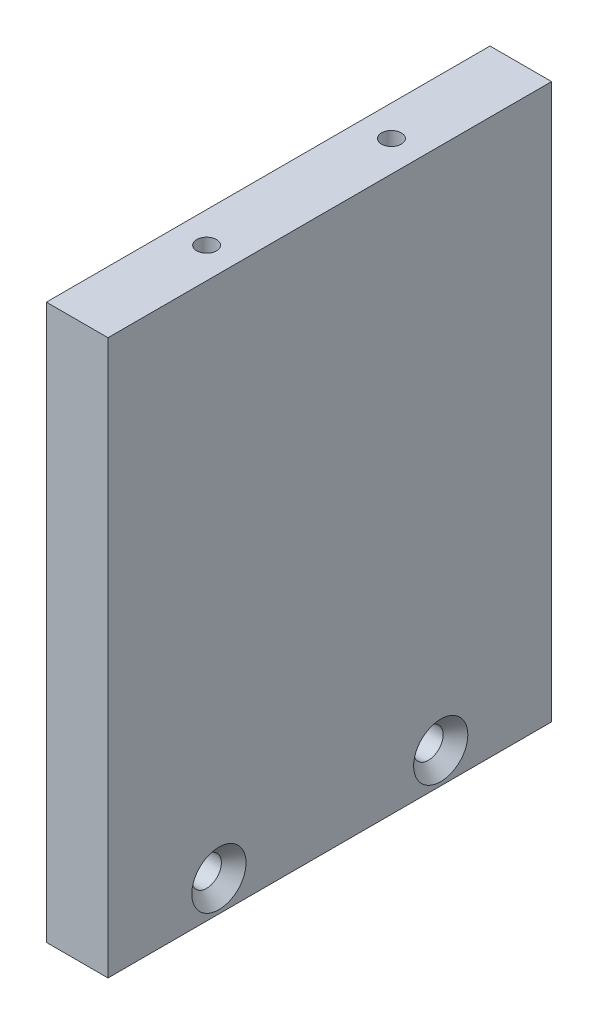
SolidWorks part; units mm, degrees
ref_plane "Front Plane" through (0, 0, 0) normal (0, 0, 1) x (1, 0, 0)
ref_plane "Top Plane" through (0, 0, 0) normal (0, 1, 0) x (1, 0, 0)
ref_plane "Right Plane" through (0, 0, 0) normal (1, 0, 0) x (0, 0, -1)
sketch "Sketch1" plane through (0, 0, 0) normal (1, 0, 0) x (0, 0, -1)
  line L1 (18, -22.5) -> (-18, -22.5)
  line L2 (18, -22.5) -> (18, 22.5)
  line L3 (18, 22.5) -> (-18, 22.5)
  line L4 (-18, -22.5) -> (-18, 22.5)
  line L5 (18, -22.5) -> (-18, 22.5) construction
  line L6 (18, 22.5) -> (-18, -22.5) construction
  point P0 (0, 0)
  dimension "D1" = 45
  dimension "D2" = 36
extrude "Boss-Extrude1" add sketch "Sketch1" along normal blind 5
sketch "Sketch2" plane through (0, 22.5, 0) normal (0, 1, 0) x (1, 0, 0)
  line L0 (2.5, 18) -> (2.5, -18) construction
  line L1 (5, 18) -> (0, 18) construction
  line L2 (5, -18) -> (0, -18) construction
  line L3 (0, 0) -> (5, 0) construction
  line L4 (5, 18) -> (5, -18) construction
  point P11 (2.5, 7.5)
  point P12 (2.5, -7.5)
  dimension "D1" = 7.5
hole_wizard "M2 Tapped Hole1" positions "Sketch3" profile "Sketch4" tap size "M2" standard "ISO"
sketch "Sketch3" plane through (0, 22.5, 0) normal (0, 1, 0) x (1, 0, 0)
  point P0 (2.5, 7.5)
  point P3 (2.5, -7.5)
sketch "Sketch4" plane through (2.5, 22.5, -7.5) normal (1, 0, 0) x (0, 0, 1)
  line L0 (0, 0) -> (0, 5.4807)
  line L1 (0, 5.4807) -> (0.8, 5)
  line L2 (0.8, 5) -> (0.8, 0)
  line L5 (0.8, 0) -> (0, 0)
  line L10 (0, 5.4807) -> (-0.8, 5) construction
  line L11 (0, -6.35) -> (0, 107.95) construction
  dimension "Tap Drill Dia." = 1.6
  dimension "Tap Drill Depth" = 5
  dimension "Drill Angle" = 118
cosmetic thread "Hole Thread1" parameters "D1"=4.6, "D2"=2
cosmetic thread "Hole Thread2" parameters "D1"=4.6, "D2"=2
sketch "Sketch5" plane through (5, 0, 0) normal (1, 0, 0) x (0, 0, -1)
  line L0 (-18, -20) -> (18, -20) construction
  line L1 (-18, 22.5) -> (-18, -22.5) construction
  line L2 (18, -22.5) -> (18, 22.5) construction
  line L3 (-18, -22.5) -> (18, -22.5) construction
  point P8 (-9, -20)
  point P9 (9, -20)
  dimension "D1" = 2.5
  dimension "D2" = 9
  dimension "D3" = 9
hole_wizard "CSK for M2 Countersunk Flat Head Screw1" positions "Sketch6" profile "Sketch7" countersink size "M2" standard "ISO" end condition through all
sketch "Sketch6" plane through (5, 0, 0) normal (1, 0, 0) x (0, 0, -1)
  point P0 (-9, -20)
  point P3 (9, -20)
sketch "Sketch7" plane through (5, -20, 9) normal (0, 1, 0) x (0, 0, -1)
  line L0 (0, 0) -> (0, 5)
  line L1 (0, 5) -> (1.2, 5)
  line L2 (1.2, 5) -> (1.2, 1)
  line L3 (1.2, 1) -> (2.2, 0)
  line L5 (2.2, 0) -> (0, 0)
  line L6 (-1.2, 1) -> (-2.2, 0) construction
  line L11 (0, -6.35) -> (0, 107.95) construction
  dimension "Thru Hole Dia." = 2.4
  dimension "Thru Hole Depth" = 5
  dimension "Near C'Sink Dia." = 4.4
  dimension "Near C'Sink Angle" = 90
